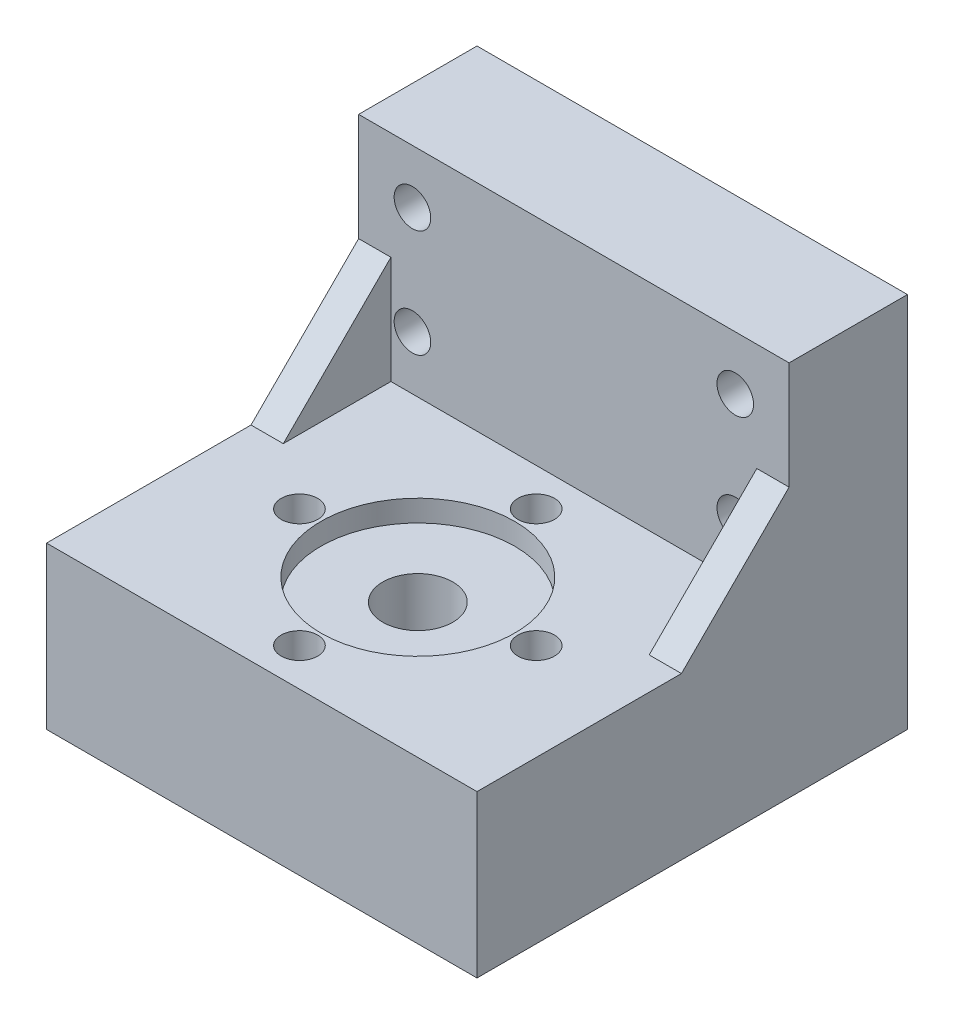
SolidWorks part; units mm, degrees
material "PLA"
ref_plane "Front Plane" through (0, 0, 0) normal (0, 0, 1) x (1, 0, 0)
ref_plane "Top Plane" through (0, 0, 0) normal (0, 1, 0) x (1, 0, 0)
ref_plane "Right Plane" through (0, 0, 0) normal (1, 0, 0) x (0, 0, -1)
sketch "Sketch1" plane through (0, 0, 0) normal (1, 0, 0) x (0, 0, -1)
  line L1 (0, 0) -> (40, 0)
  line L2 (0, 0) -> (0, 15)
  line L3 (0, 15) -> (29, 15)
  line L4 (40, 0) -> (40, 15)
  line L6 (40, 15) -> (40, 35)
  line L7 (40, 35) -> (29, 35)
  line L8 (29, 15) -> (29, 35)
  dimension "D2" = 11
  dimension "D1" = 20
  dimension "D3" = 40
  dimension "D4" = 15
extrude "Boss-Extrude1" add sketch "Sketch1" along normal blind 40 contours L3 L8 L7 L6 L4 L1 L2
sketch "Sketch2" plane through (0, 15, 0) normal (0, 1, 0) x (1, 0, 0)
  line L1 (0, 0) -> (0, 29) construction
  line L3 (0, 14.5) -> (40, 14.5) construction
  line L4 (40, 0) -> (0, 0) construction
  line L5 (20, 29) -> (20, 0) construction
  line L6 (40, 29) -> (0, 29) construction
  circle A1 centre (20, 14.5) radius 9
  point P4 (20, 0)
  dimension "D1" = 18
extrude "Cut-Extrude8" cut sketch "Sketch2" against normal blind 2
sketch "Sketch6" plane through (0, 13, 0) normal (0, 1, 0) x (1, 0, 0)
  circle A0 centre (20, 14.5) radius 3.25
  circle A1 centre (20, 14.5) radius 9 construction
  dimension "D1" = 6.5
extrude "Cut-Extrude9" cut sketch "Sketch6" against normal through all
sketch "Sketch7" plane through (0, 15, 0) normal (0, 1, 0) x (1, 0, 0)
  line L0 (0, 14.5) -> (40, 14.5) construction
  line L1 (0, 0) -> (0, 29) construction
  line L2 (40, 0) -> (40, 29) construction
  line L3 (20, 29) -> (20, 0) construction
  line L4 (40, 29) -> (0, 29) construction
  line L5 (40, 0) -> (0, 0) construction
  circle A7 centre (31, 14.5) radius 1.7
  circle A8 centre (20, 25.5) radius 1.7
  circle A9 centre (9, 14.5) radius 1.7
  circle A10 centre (20, 3.5) radius 1.7
  point P20 (20, 14.5)
  dimension "D5" = 3.4
  dimension "D6" = 3.4
  dimension "D7" = 3.4
  dimension "D8" = 3.4
  dimension "D1" = 11
  dimension "D2" = 11
  dimension "D3" = 11
  dimension "D4" = 11
extrude "Cut-Extrude10" cut sketch "Sketch7" against normal through all
sketch "Sketch8" plane through (0, 0, -29) normal (0, 0, 1) x (1, 0, 0)
  line L0 (0, 15) -> (0, 35) construction
  line L1 (40, 35) -> (0, 35) construction
  line L3 (40, 15) -> (0, 15) construction
  line L4 (40, 15) -> (40, 35) construction
  circle A1 centre (35, 30) radius 1.7
  circle A3 centre (35, 20) radius 1.7
  circle A4 centre (5, 30) radius 1.7
  circle A5 centre (5, 20) radius 1.7
  dimension "D1" = 3.4
  dimension "D2" = 5
  dimension "D3" = 5
  dimension "D4" = 5
  dimension "D5" = 5
  dimension "D6" = 5
  dimension "D7" = 5
  dimension "D8" = 5
  dimension "D9" = 5
extrude "Cut-Extrude11" cut sketch "Sketch8" against normal through all
sketch "Sketch9" plane through (40, 0, 0) normal (1, 0, 0) x (0, 0, -1)
  line L3 (29, 25) -> (29, 15)
  line L4 (29, 15) -> (19, 15)
  line L5 (0, 15) -> (29, 15) construction
  line L6 (19, 15) -> (29, 25)
  dimension "D2" = 10
  dimension "D1" = 10
extrude "Boss-Extrude3" add sketch "Sketch9" against normal blind 3
ref_plane "Plane2" through (20, 0, 0) normal (-1, 0, 0) x (0, 0, 1)
mirror "Mirror3" about plane through (20, 0, 0) normal (-1, 0, 0) of "Boss-Extrude3"
equation "\"MountWidth\"= 40mm"
equation "\"FeatureThickness\"= 15mm"
equation "\"Gusset Size\"= 10mm"
equation "\"BoltClearance\"= 3.4mm"
equation "\"D5@Sketch7\"=\"BoltClearance\""
equation "\"D6@Sketch7\"=\"BoltClearance\""
equation "\"D7@Sketch7\"=\"BoltClearance\""
equation "\"D8@Sketch7\"=\"BoltClearance\""
equation "\"D1@Sketch9\"=\"Gusset Size\""
equation "\"D2@Sketch9\"=\"Gusset Size\""
equation "\"D1@Sketch8\"=\"BoltClearance\""
equation "\"D4@Sketch1\"=\"FeatureThickness\""
equation "\"D3@Sketch1\"=\"MountWidth\""
